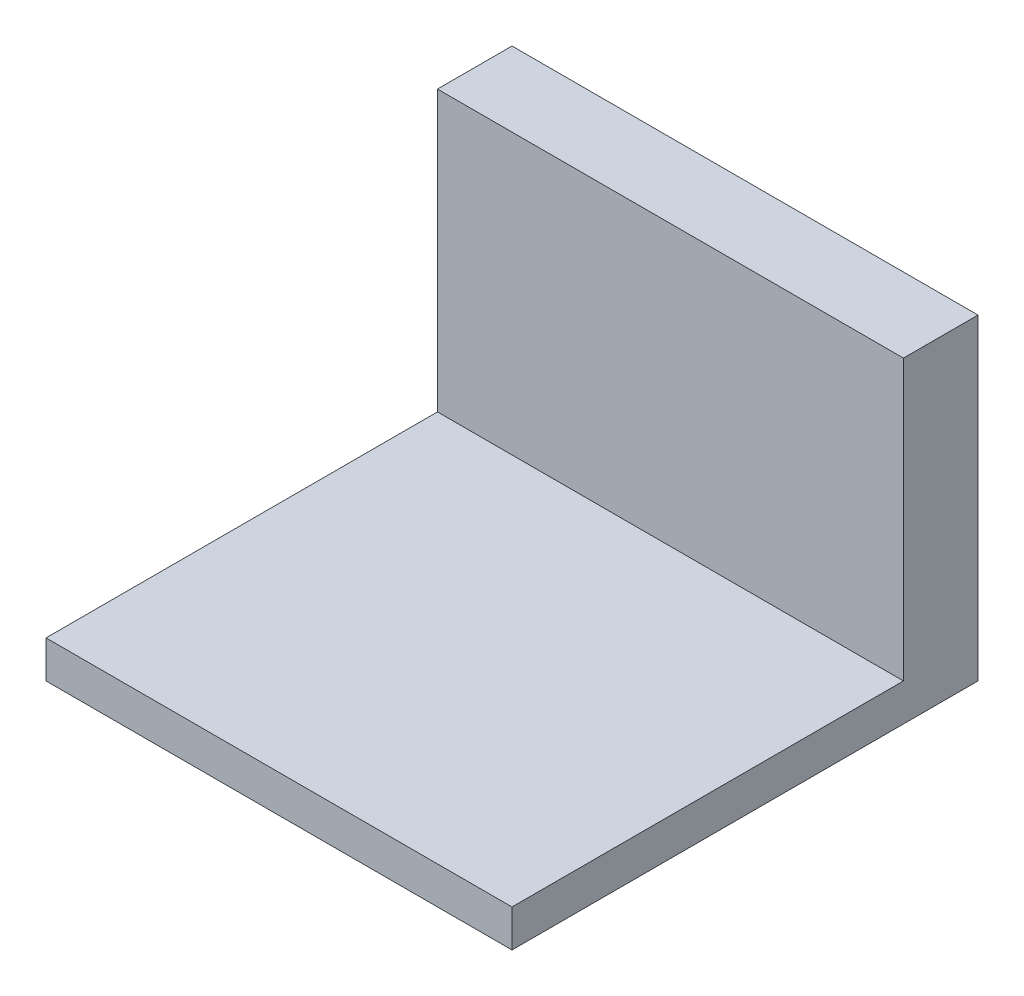
SolidWorks part; units mm, degrees
ref_plane "Front Plane" through (0, 0, 0) normal (0, 0, 1) x (1, 0, 0)
ref_plane "Top Plane" through (0, 0, 0) normal (0, 1, 0) x (1, 0, 0)
ref_plane "Right Plane" through (0, 0, 0) normal (1, 0, 0) x (0, 0, -1)
sketch "Sketch1" plane through (0, 0, 0) normal (0, 1, 0) x (1, 0, 0)
  line L1 (250, -250) -> (-250, -250)
  line L2 (250, -250) -> (250, 250)
  line L3 (250, 250) -> (-250, 250)
  line L4 (-250, -250) -> (-250, 250)
  line L5 (250, -250) -> (-250, 250) construction
  line L6 (250, 250) -> (-250, -250) construction
  point P1 (0, 0)
extrude "Boss-Extrude1" add sketch "Sketch1" along normal blind 40
sketch "Sketch2" plane through (0, 40, 0) normal (0, 1, 0) x (1, 0, 0)
  line L0 (250, -250) -> (250, 250) construction
  line L1 (-250, 250) -> (250, 250)
  line L2 (-250, 250) -> (-250, 170.0094)
  line L3 (-250, 170.0094) -> (250, 170.0094)
  line L4 (250, 250) -> (250, 170.0094)
extrude "Boss-Extrude2" add sketch "Sketch2" along normal blind 300
